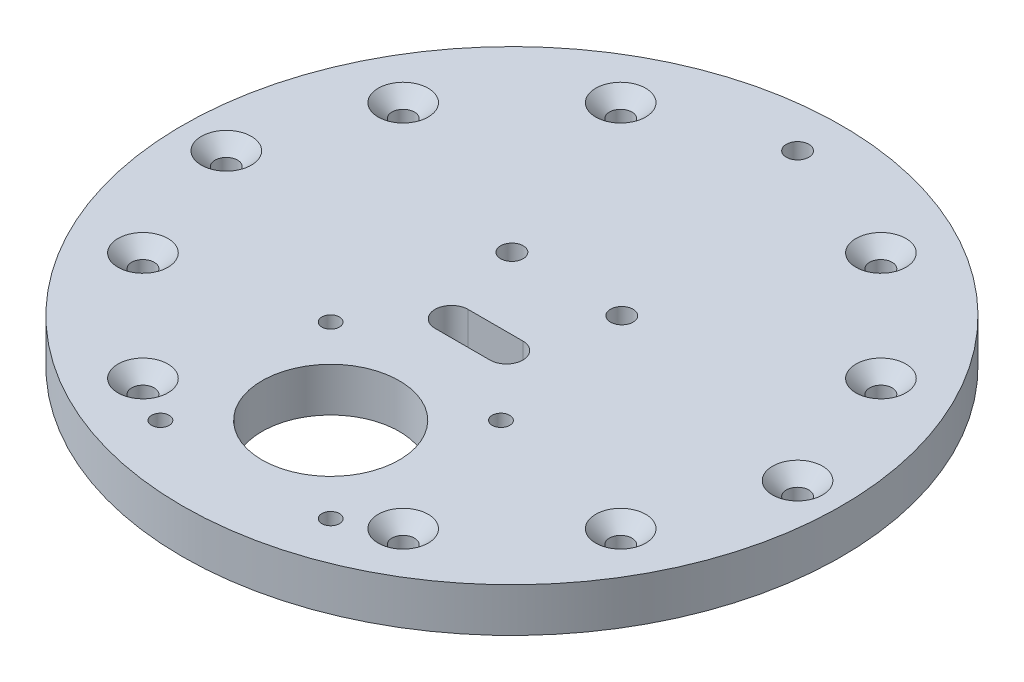
SolidWorks part; units mm, degrees
ref_plane "Front Plane" through (0, 0, 0) normal (0, 0, 1) x (1, 0, 0)
ref_plane "Top Plane" through (0, 0, 0) normal (0, 1, 0) x (1, 0, 0)
ref_plane "Right Plane" through (0, 0, 0) normal (1, 0, 0) x (0, 0, -1)
sketch "Sketch1" plane through (0, 0, 0) normal (0, 1, 0) x (1, 0, 0)
  circle A0 centre (0, 0) radius 60
  dimension "D1" = 120
extrude "Boss-Extrude1" add sketch "Sketch1" along normal blind 8
sketch "Sketch2" plane through (0, 8, 0) normal (0, 1, 0) x (1, 0, 0)
  line L1 (15.5, -48.5) -> (-15.5, -48.5) construction
  line L2 (15.5, -48.5) -> (15.5, -17.5) construction
  line L3 (15.5, -17.5) -> (-15.5, -17.5) construction
  line L4 (-15.5, -48.5) -> (-15.5, -17.5) construction
  line L5 (15.5, -48.5) -> (-15.5, -17.5) construction
  line L6 (15.5, -17.5) -> (-15.5, -48.5) construction
  circle A0 centre (0, -33) radius 12.5
  circle A1 centre (-15.5, -48.5) radius 1.6
  circle A2 centre (15.5, -48.5) radius 1.6
  circle A3 centre (15.5, -17.5) radius 1.6
  circle A4 centre (-15.5, -17.5) radius 1.6
  dimension "D1" = 25
  dimension "D5" = 3.2
  dimension "D6" = 3.2
  dimension "D7" = 3.2
  dimension "D8" = 3.2
  dimension "D2" = 33
  dimension "D3" = 31
  dimension "D4" = 31
extrude "Cut-Extrude1" cut sketch "Sketch2" against normal through all
sketch "Sketch3" plane through (0, 8, 0) normal (0, 1, 0) x (1, 0, 0)
  line L0 (0, 0) -> (0, -60) construction
  line L1 (0, 0) -> (-33.5876, -33.5876) construction
  line L2 (-9.8995, 9.8995) -> (-43.4871, -23.6881) construction
  line L3 (9.8995, -9.8995) -> (-23.6881, -43.4871) construction
  circle A0 centre (0, 0) radius 60 construction
  circle A1 centre (-33.5876, -33.5876) radius 5 construction
  circle A2 centre (-43.4871, -23.6881) radius 2.05
  circle A3 centre (-23.6881, -43.4871) radius 2.05
  dimension "D5" = 4.1
  dimension "D6" = 4.1
  dimension "D7" = 10
  dimension "D1" = 45
  dimension "D2" = 47.5
  dimension "D3" = 14
  dimension "D4" = 14
extrude "Cut-Extrude2" cut sketch "Sketch3" against normal through all contours A2 | A3
pattern_circular "CirPattern1" count 4 over 360 about axis through (0, 0, 0) along (0, 1, 0) of "Cut-Extrude2"
sketch "Sketch4" plane through (0, 8, 0) normal (0, 1, 0) x (1, 0, 0)
  circle A0 centre (-52, 0) radius 2.05
  circle A1 centre (52, 0) radius 2.05
  circle A2 centre (0, 52) radius 2.05
  point P4 (0, 0)
  dimension "D3" = 4.1
  dimension "D4" = 4.1
  dimension "D6" = 4.1
  dimension "D1" = 52
  dimension "D2" = 52
  dimension "D5" = 52
extrude "Cut-Extrude3" cut sketch "Sketch4" against normal through all
sketch "Sketch5" plane through (0, 8, 0) normal (0, 1, 0) x (1, 0, 0)
  line L0 (-5, -6) -> (5, -6) construction
  line L1 (-5, -3) -> (5, -3)
  line L2 (-5, -9) -> (5, -9)
  circle A0 centre (-10, 10) radius 2.05
  circle A1 centre (10, 10) radius 2.05
  arc A2 (-5, -3) -> (-5, -9) centre (-5, -6) ccw
  arc A3 (5, -9) -> (5, -3) centre (5, -6) ccw
  point P6 (0, -6)
  point P11 (0, 0)
  point P12 (0, 0)
  dimension "D1" = 3
  dimension "D2" = 4.1
  dimension "D3" = 4.1
  dimension "D4" = 13
  dimension "D5" = 3
  dimension "D6" = 10
  dimension "D7" = 10
  dimension "D8" = 10
extrude "Cut-Extrude4" cut sketch "Sketch5" against normal through all
sketch "Sketch6" plane through (0, 0, 0) normal (0, -1, 0) x (1, 0, 0)
  line L1 (0, -38) -> (8, -38)
  line L2 (0, -38) -> (0, -18)
  line L3 (0, -18) -> (8, -18)
  line L4 (8, -38) -> (8, -18)
  line L5 (0, -38) -> (8, -18) construction
  line L6 (0, -18) -> (8, -38) construction
  point P0 (4, -28)
  point P5 (0, 0)
  dimension "D1" = 20
  dimension "D2" = 8
  dimension "D3" = 18
extrude "Boss-Extrude2" add sketch "Sketch6" along normal blind 18 contours L3 L4 L1 L2
chamfer "Chamfer1" distance 5 angle 45 1 edges at (8, 0, -28)
sketch "Sketch7" plane through (8, 0, 0) normal (1, 0, 0) x (0, 0, -1)
  line L0 (38, -18) -> (18, -18) construction
  line L1 (38, -18) -> (38, -5) construction
  circle A0 centre (23.25, -10.5) radius 1.6
  circle A1 centre (32.75, -10.5) radius 1.6
  point P6 (0, 0)
  dimension "D1" = 7.5
  dimension "D2" = 3.2
  dimension "D3" = 3.2
  dimension "D4" = 9.5
  dimension "D5" = 5.25
extrude "Cut-Extrude5" cut sketch "Sketch7" against normal through all
hole_wizard "CSK for M4 Countersunk Flat Head Screw1" positions "3DSketch1" profile "Sketch9" countersink size "M4" standard "ISO"
sketch3d "3DSketch1"
  line L0 (-52, 0, 0) -> (-52, 8, 0) construction
  line L1 (-43.4871, 0, 23.6881) -> (-43.4871, 8, 23.6881) construction
  line L2 (-23.6881, 0, 43.4871) -> (-23.6881, 8, 43.4871) construction
  line L3 (23.6881, 0, 43.4871) -> (23.6881, 8, 43.4871) construction
  line L4 (43.4871, 0, 23.6881) -> (43.4871, 8, 23.6881) construction
  line L5 (52, 0, 0) -> (52, 8, 0) construction
  line L6 (43.4871, 0, -23.6881) -> (43.4871, 8, -23.6881) construction
  line L7 (23.6881, 0, -43.4871) -> (23.6881, 8, -43.4871) construction
  line L8 (-23.6881, 0, -43.4871) -> (-23.6881, 8, -43.4871) construction
  line L9 (-43.4871, 0, -23.6881) -> (-43.4871, 8, -23.6881) construction
  point P0 (-52, 8, 0)
  point P4 (-43.4871, 8, 23.6881)
  point P8 (-23.6881, 8, 43.4871)
  point P12 (23.6881, 8, 43.4871)
  point P16 (43.4871, 8, 23.6881)
  point P20 (52, 8, 0)
  point P24 (43.4871, 8, -23.6881)
  point P28 (23.6881, 8, -43.4871)
  point P32 (-23.6881, 8, -43.4871)
  point P36 (-43.4871, 8, -23.6881)
sketch "Sketch9" plane through (-52, 8, 0) normal (1, 0, 0) x (0, 0, 1)
  line L0 (0, 0) -> (0, 9.2308)
  line L1 (0, 9.2308) -> (2.05, 7.999)
  line L2 (2.05, 7.999) -> (2.05, 2.5)
  line L3 (2.05, 2.5) -> (4.55, 0)
  line L5 (4.55, 0) -> (0, 0)
  line L6 (-2.05, 2.5) -> (-4.55, 0) construction
  line L10 (0, 9.2308) -> (-2.05, 7.999) construction
  line L11 (0, -6.35) -> (0, 107.95) construction
  dimension "Hole Dia." = 4.1
  dimension "Hole Depth" = 7.999
  dimension "Near C'Sink Dia." = 9.1
  dimension "Near C'Sink Angle" = 90
  dimension "Drill Angle" = 118
